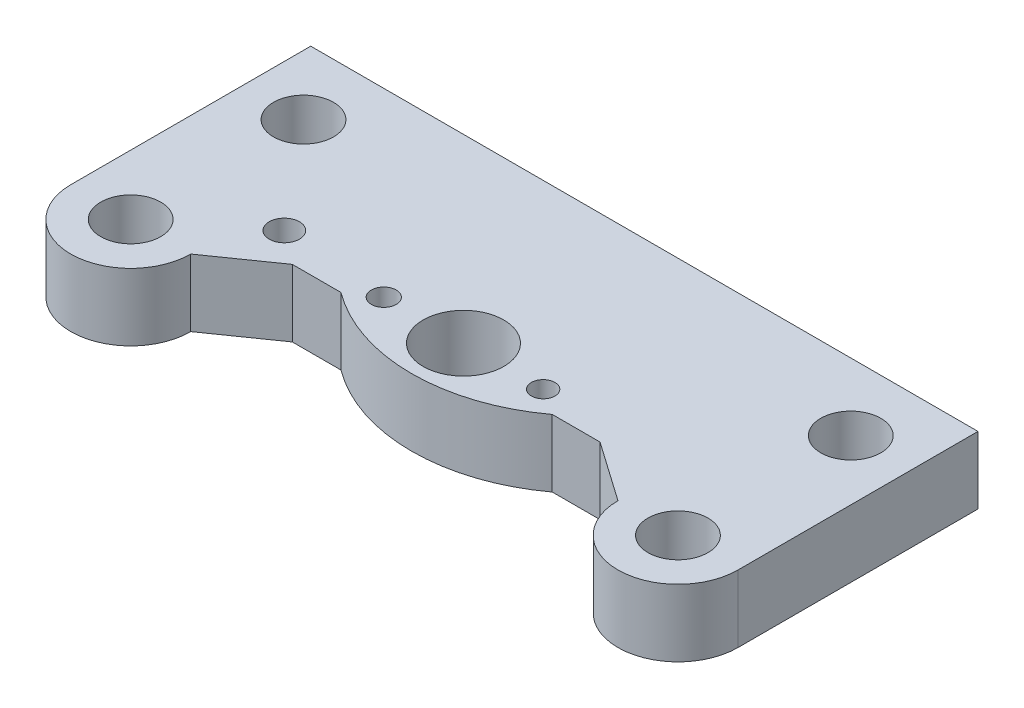
SolidWorks part; units mm, degrees
material "Custom Plastic"
ref_plane "X-Y Datum" through (0, 0, 0) normal (0, 0, 1) x (1, 0, 0)
ref_plane "X-Z Datum" through (0, 0, 0) normal (0, 1, 0) x (1, 0, 0)
ref_plane "Y-Z Datum" through (0, 0, 0) normal (1, 0, 0) x (0, 0, -1)
sketch "Sketch1" plane through (0, 0, 0) normal (0, 1, 0) x (1, 0, 0)
  line L0 (72.39, 0) -> (0, 0) construction
  line L1 (80.3275, 13.97) -> (-7.9375, 13.97) construction
  line L4 (80.3275, 31.75) -> (-7.9375, 31.75)
  line L6 (72.39, 22.86) -> (0, 22.86) construction
  line L7 (80.3275, 31.75) -> (80.3275, 13.97)
  line L8 (-7.9375, 31.75) -> (-7.9375, 13.97)
  line L10 (80.3275, 13.97) -> (80.3275, 0)
  line L14 (-7.9375, 0) -> (-7.9375, 13.97)
  line L15 (7.9375, 0) -> (15.844, 5.5362)
  line L18 (64.4525, 0) -> (56.546, 5.5362)
  line L25 (56.546, 5.5362) -> (50.2217, 5.5362)
  line L28 (15.844, 5.5362) -> (22.2758, 5.5362)
  circle A0 centre (0, 0) radius 3.9688
  circle A1 centre (72.39, 0) radius 3.9688
  circle A2 centre (72.39, 22.86) radius 3.9688
  circle A3 centre (0, 22.86) radius 3.9688
  arc A4 (80.3275, 0) -> (64.4525, 0) centre (72.39, 0) cw
  arc A5 (7.9375, 0) -> (-7.9375, 0) centre (0, 0) cw
  circle A6 centre (11.43, 8.89) radius 2
  circle A7 centre (25.654, 7.8222) radius 1.651
  circle A8 centre (46.736, 7.8222) radius 1.5596
  circle A11 centre (36.195, 7.8222) radius 5.334
  arc A12 (22.2758, 5.5362) -> (50.2217, 5.5362) centre (36.2488, 24.3136) ccw
  dimension "D1" = 7.9375
  dimension "D2" = 7.9375
  dimension "D7" = 7.9375
  dimension "D8" = 7.9375
  dimension "D12" = 4
  dimension "D10" = 10.541
  dimension "D17" = 10.541
  dimension "D3" = 72.39
  dimension "D4" = 17.78
  dimension "D5" = 8.89
  dimension "D6" = 31.75
  dimension "D9" = 72.39
  dimension "D11" = 7.8222
  dimension "D13" = 8.89
  dimension "D14" = 11.43
  dimension "D15" = 7.8222
  dimension "D16" = 21.082
extrude "Boss-Extrude1" add sketch "Sketch1" against normal blind 8.89
